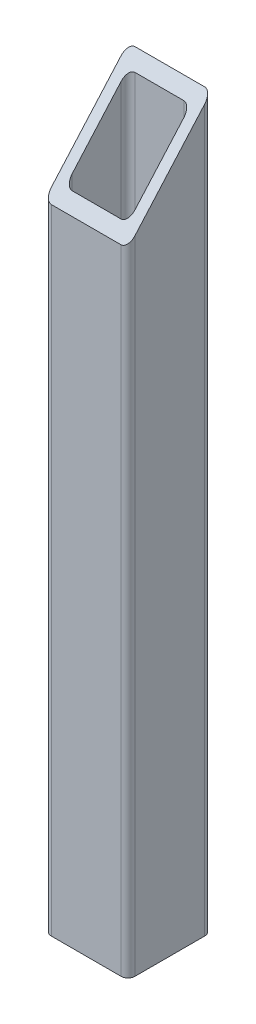
SolidWorks part; units mm, degrees
material "6061-T6 (SS)"
ref_plane "Front Plane" through (0, 0, 0) normal (0, 0, 1) x (1, 0, 0)
ref_plane "Top Plane" through (0, 0, 0) normal (0, 1, 0) x (1, 0, 0)
ref_plane "Right Plane" through (0, 0, 0) normal (1, 0, 0) x (0, 0, -1)
sketch "Sketch1" plane through (0, 0, 0) normal (0, 1, 0) x (1, 0, 0)
  line L0 (9.525, 9.525) -> (-9.525, 9.525)
  line L1 (12.7, -12.7) -> (-12.7, -12.7)
  line L2 (12.7, -12.7) -> (12.7, 12.7)
  line L3 (12.7, 12.7) -> (-12.7, 12.7)
  line L4 (-12.7, -12.7) -> (-12.7, 12.7)
  line L5 (12.7, -12.7) -> (-12.7, 12.7) construction
  line L6 (12.7, 12.7) -> (-12.7, -12.7) construction
  line L7 (-9.525, -9.525) -> (-9.525, 9.525)
  line L8 (9.525, -9.525) -> (-9.525, -9.525)
  line L9 (9.525, -9.525) -> (9.525, 9.525)
  point P0 (0, 0)
  dimension "D1" = 25.4
  dimension "D2" = 25.4
  dimension "D3" = 3.175
extrude "Boss-Extrude1" add sketch "Sketch1" along normal blind 1219.2
fillet "Fillet1" radius 2.1082 8 edges at (9.525, 609.6, -9.525) (-9.525, 609.6, -9.525) (-9.525, 609.6, 9.525) (9.525, 609.6, 9.525) (12.7, 609.6, -12.7) (-12.7, 609.6, -12.7) (-12.7, 609.6, 12.7) (12.7, 609.6, 12.7)
sketch "Sketch2" plane through (12.7, 0, 0) normal (1, 0, 0) x (0, 0, -1)
  line L1 (-38.375, 0) -> (123.0295, 0)
  line L2 (-38.375, 0) -> (-38.375, 228.6)
  line L3 (-38.375, 228.6) -> (123.0295, 228.6)
  line L4 (123.0295, 0) -> (123.0295, 228.6)
  dimension "D1" = 228.6
extrude "Cut-Extrude1" cut sketch "Sketch2" against normal through all flip side to cut
sketch "Sketch3" plane through (12.7, 0, 0) normal (1, 0, 0) x (0, 0, -1)
  line L0 (-201.676, 0) -> (-14.873, 211.8147)
  line L1 (12.7, 228.6) -> (12.7, 0) construction
  line L3 (-190.768, -9.62) -> (10.8383, 218.98)
  line L4 (-190.768, -9.62) -> (-201.676, 0)
  line L5 (10.8383, 218.98) -> (26.3609, 236.581)
  line L6 (26.3609, 236.581) -> (15.4529, 246.201)
  line L7 (15.4529, 246.201) -> (-0.0698, 228.6)
  line L8 (-0.0698, 228.6) -> (-14.873, 228.6)
  line L9 (-14.873, 228.6) -> (-14.873, 211.8147)
  line L10 (-201.676, 0) -> (-0.0698, 228.6) construction
  dimension "D1" = 214.376
  dimension "D2" = 304.8
  dimension "D3" = 14.544
extrude "Cut-Extrude2" cut sketch "Sketch3" against normal through all
